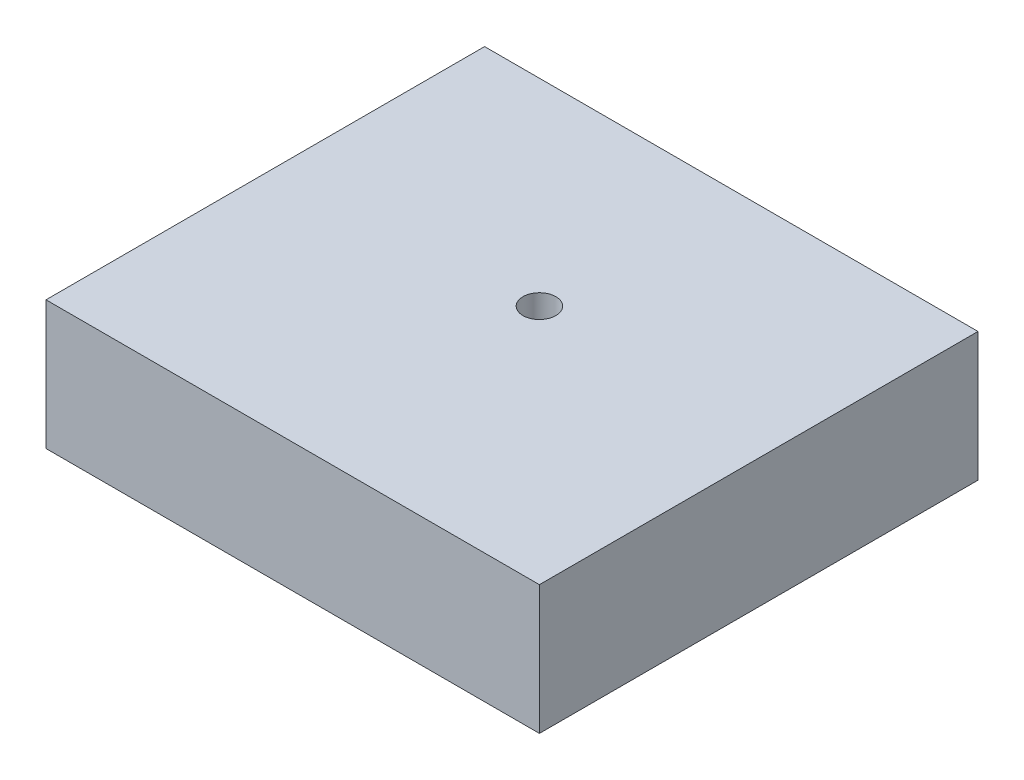
SolidWorks part; units mm, degrees
ref_plane "Front Plane" through (0, 0, 0) normal (0, 0, 1) x (1, 0, 0)
ref_plane "Top Plane" through (0, 0, 0) normal (0, 1, 0) x (1, 0, 0)
ref_plane "Right Plane" through (0, 0, 0) normal (1, 0, 0) x (0, 0, -1)
sketch "Sketch1" plane through (0, 0, 0) normal (0, 1, 0) x (1, 0, 0)
  line L1 (0, 0) -> (18, 0)
  line L2 (0, 0) -> (0, 16)
  line L3 (0, 16) -> (18, 16)
  line L4 (18, 0) -> (18, 16)
  circle A0 centre (9.2, 8.8) radius 0.6
  dimension "D3" = 1.2
  dimension "D1" = 18
  dimension "D2" = 16
  dimension "D4" = 7.2
  dimension "D5" = 8.8
extrude "Boss-Extrude1" add sketch "Sketch1" along normal blind 4.7
